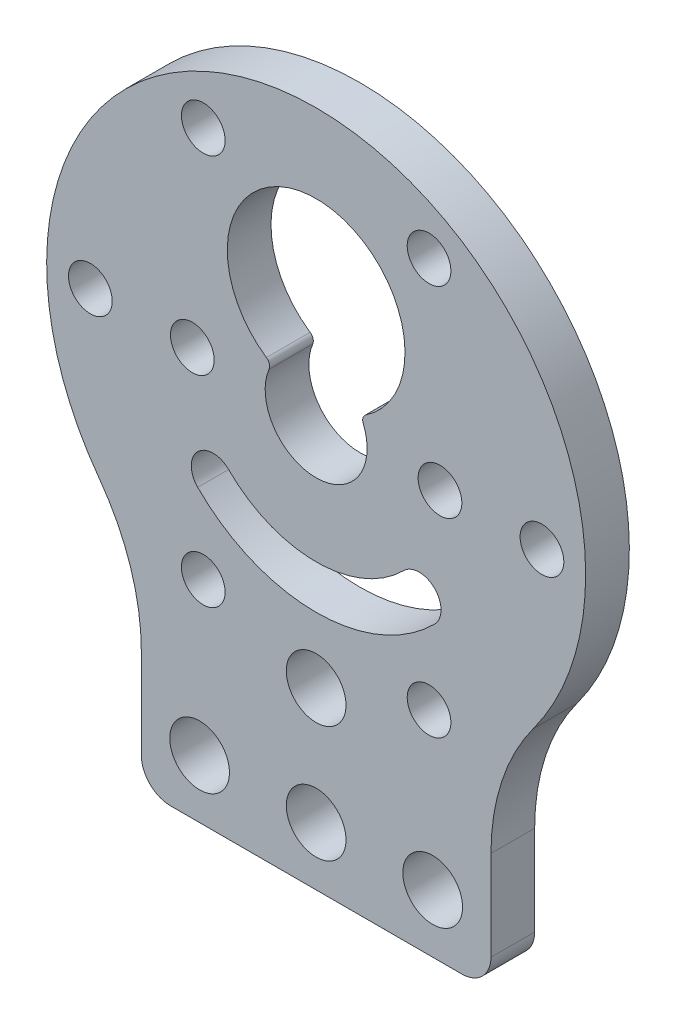
SolidWorks part; units mm, degrees
ref_plane "Front Plane" through (0, 0, 0) normal (0, 0, 1) x (1, 0, 0)
ref_plane "Top Plane" through (0, 0, 0) normal (0, 1, 0) x (1, 0, 0)
ref_plane "Right Plane" through (0, 0, 0) normal (1, 0, 0) x (0, 0, -1)
ref_plane "Plane1" through (0, 0, 3) normal (0, 0, 1) x (1, 0, 0)
sketch "Sketch1" plane through (0, 0, 3) normal (0, 0, 1) x (1, 0, 0)
  line L0 (-12, -26.8305) -> (-12, -33)
  line L1 (-10, -35) -> (10, -35)
  line L2 (12, -33) -> (12, -26.8305)
  circle A0 centre (8, -31) radius 2.05
  circle A1 centre (-8, -31) radius 2.05
  circle A2 centre (0, -31) radius 2.05
  circle A3 centre (-7.75, 6.4234) radius 1.5
  circle A4 centre (7.75, 6.4234) radius 1.5
  circle A5 centre (15.5, -7) radius 1.5
  circle A6 centre (7.75, -20.4234) radius 1.5
  circle A7 centre (-7.75, -20.4234) radius 1.5
  circle A8 centre (-15.5, -7) radius 1.5
  arc A9 (3.2333, -5.66) -> (-3.2333, -5.66) centre (0, -7) cw
  arc A10 (-3.2333, -5.66) -> (-3.4153, -5.0543) centre (-3.6952, -5.4686) ccw
  arc A11 (-3.4153, -5.0543) -> (3.4153, -5.0543) centre (0, 0) cw
  arc A12 (3.4153, -5.0543) -> (3.2333, -5.66) centre (3.6952, -5.4686) ccw
  circle A13 centre (-8.5, -7) radius 1.5
  circle A14 centre (0, -23) radius 2.05
  circle A15 centre (8.5, -7) radius 1.5
  arc A16 (6.0104, -13.0104) -> (8.1317, -15.1317) centre (7.0711, -14.0711) cw
  arc A17 (8.1317, -15.1317) -> (-8.1317, -15.1317) centre (0, -7) cw
  arc A18 (-8.1317, -15.1317) -> (-6.0104, -13.0104) centre (-7.0711, -14.0711) cw
  arc A19 (-6.0104, -13.0104) -> (6.0104, -13.0104) centre (0, -7) ccw
  arc A20 (-12, -33) -> (-10, -35) centre (-10, -33) ccw
  arc A21 (10, -35) -> (12, -33) centre (10, -33) ccw
  arc A22 (12, -26.8305) -> (14.9104, -17.9512) centre (27, -26.8305) cw
  arc A23 (14.9104, -17.9512) -> (-14.9104, -17.9512) centre (0, -7) ccw
  arc A24 (-14.9104, -17.9512) -> (-12, -26.8305) centre (-27, -26.8305) cw
  circle A25 centre (0, -7) radius 15.5 construction
  dimension "D1" = 17
  dimension "D2" = 31
extrude "Boss-Extrude1" add sketch "Sketch1" against normal blind 3
